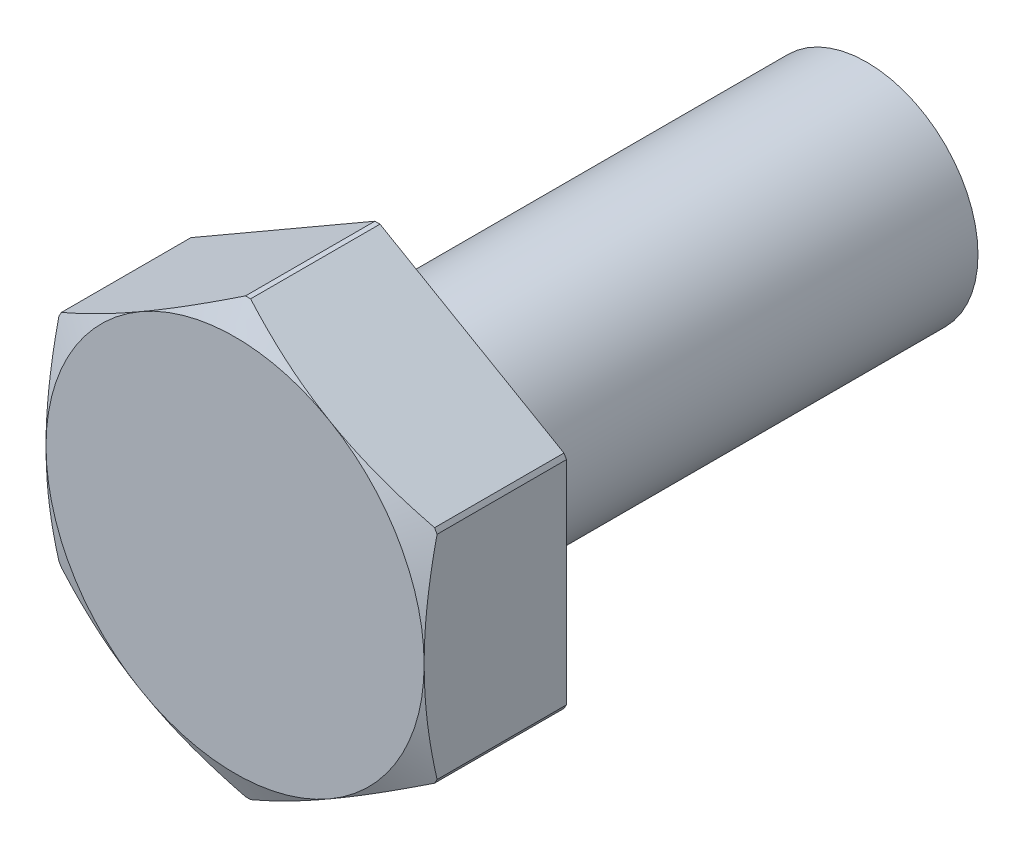
SolidWorks part; units mm, degrees
material "AISI 304"
ref_plane "Front" through (0, 0, 0) normal (0, 0, 1) x (1, 0, 0)
ref_plane "Top" through (0, 0, 0) normal (0, 1, 0) x (1, 0, 0)
ref_plane "Right" through (0, 0, 0) normal (1, 0, 0) x (0, 0, -1)
sketch "Sketch1" plane through (0, 0, 0) normal (1, 0, 0) x (0, 0, -1)
  line L0 (0, 0) -> (-6.4, 0) construction
  line L1 (0, 0) -> (22, 0)
  line L2 (0, 0) -> (0, 5)
  line L3 (0, 5) -> (22, 5)
  line L4 (22, 0) -> (22, 5)
  line L5 (0, -5) -> (22, -5) construction
  point P7 (14.4062, 5)
  point P8 (14.4062, -5)
  dimension "D1" = 22
  dimension "Thread Dia" = 10
  dimension "Length" = 22
  dimension "Head Height" = 6.4
  dimension "Note Dim" = 7.5938
revolve "Revolve1" add sketch "Sketch1" angle 360 about L0
sketch "Sketch6" plane through (0, 0, -22) normal (0, 0, -1) x (-1, 0, 0)
  circle A0 centre (0, 0) radius 5 construction
  circle A1 centre (0, 0) radius 5
sketch "Sketch2" plane through (0, 0, 0) normal (1, 0, 0) x (0, 0, -1)
  line L1 (21.9062, 5.1624) -> (22.6562, 3.8633) construction
  line L2 (22.6562, 3.8633) -> (23.4062, 5.1624) construction
  line L3 (23.4062, 5.1624) -> (21.9062, 5.1624) construction
  line L4 (22.6562, 5.1624) -> (22.6562, 3.8633) construction
  line L5 (22, 5) -> (23.3125, 5) construction
  line L6 (23.3125, 5) -> (22.8438, 4.1881)
  line L7 (22.8438, 4.1881) -> (22.4688, 4.1881)
  line L8 (23.3125, 5) -> (21.9062, 5.1624)
  line L9 (21.9062, 5.1624) -> (22.4688, 4.1881)
  dimension "D2" = 0.375
  dimension "D3" = 1.3125
  dimension "D1" = 60
sketch "Sketch3" plane through (0, 0, 0) normal (1, 0, 0) x (0, 0, -1)
  line L0 (22, 4.1881) -> (20.2589, 5)
  line L1 (20.2589, 5) -> (22, 5)
  line L2 (22, 5) -> (22, 4.1881)
  line L3 (0, 5) -> (22, 5) construction
  line L4 (22, 0) -> (22, 5) construction
  line L5 (20.2589, 0) -> (0, 0) construction
  line L6 (20.2589, 5) -> (20.2589, -5) construction
  line L7 (0, -5) -> (22, -5) construction
  line L8 (22, -5) -> (22, 5) construction
  line L9 (22, 4.1881) -> (22.4688, 4.1881) construction
  dimension "D1" = 25
  dimension "D2" = 10
sketch "Sketch4" plane through (0, 0, 0) normal (0, 0, 1) x (1, 0, 0)
  line L1 (0, 9.815) -> (-8.5, 4.9075)
  line L2 (-8.5, 4.9075) -> (-8.5, -4.9075)
  line L3 (-8.5, -4.9075) -> (0, -9.815)
  line L4 (0, -9.815) -> (8.5, -4.9075)
  line L5 (8.5, -4.9075) -> (8.5, 4.9075)
  line L6 (8.5, 4.9075) -> (0, 9.815)
  circle A0 centre (0, 0) radius 8.5 construction
  circle A1 centre (0, 0) radius 8.5 construction
  dimension "Head Dia" = 17
extrude "Extrude1" add sketch "Sketch4" along normal up to vertex (18.7 mm away)
sketch "Sketch5" plane through (0, 0, 0) normal (1, 0, 0) x (0, 0, -1)
  line L0 (-6.4, 8.5) -> (-5.8175, 9.7492)
  line L1 (0, 9.815) -> (-6.4, 9.815)
  line L2 (-6.4, 9.815) -> (-6.4, 8.5)
  line L3 (0, 0) -> (-6.4, 0) construction
  line L4 (-6.4, 9.815) -> (0, 9.815) construction
  line L5 (-6.4, 4.9075) -> (-6.4, 9.815) construction
  line L6 (-5.8175, 9.7492) -> (0, 9.7492)
  line L7 (-6.4, 8.5) -> (0, 8.5) construction
  line L10 (0, 9.7492) -> (0, 9.815)
  line L11 (0, 4.9075) -> (0, 9.815) construction
  dimension "D4" = 0.0657
  dimension "D1" = 25
  dimension "D3" = 1.315
  dimension "D5" = 6.4
  dimension "D6" = 22
revolve "Cut-Revolve3" cut sketch "Sketch5" angle 360 about L3
equation "\"D2@Sketch2\"=\"Thread Pitch@Sketch2\"*1/4"
equation "\"D3@Sketch2\"=\"Thread Pitch@Sketch2\"*7/8"
